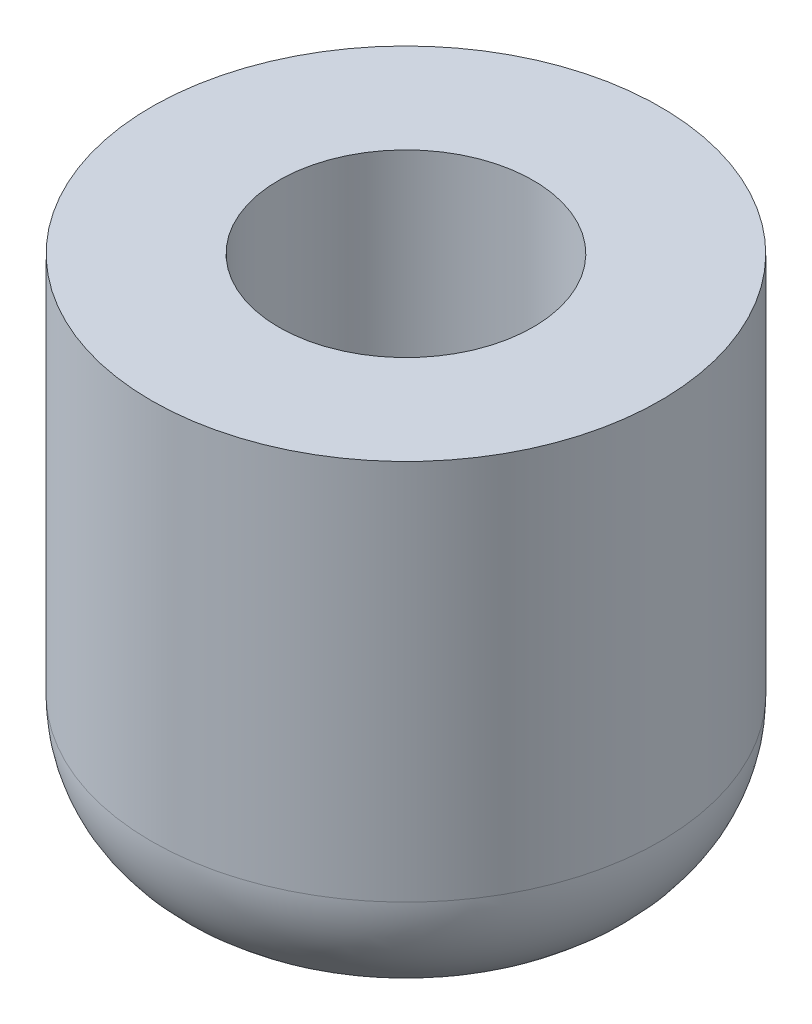
SolidWorks part; units mm, degrees
material "POLYURETHANE (11671)"
ref_plane "Front" through (0, 0, 0) normal (0, 0, 1) x (1, 0, 0)
ref_plane "Top" through (0, 0, 0) normal (0, 1, 0) x (1, 0, 0)
ref_plane "Right" through (0, 0, 0) normal (1, 0, 0) x (0, 0, -1)
sketch "Sketch1" plane through (0, 0, 0) normal (0, 1, 0) x (1, 0, 0)
  circle A0 centre (0, 0) radius 6.35
  dimension "D1" = 12.7
extrude "Boss-Extrude1" add sketch "Sketch1" along normal mid plane 12.7
sketch "Sketch2" plane through (0, 6.35, 0) normal (0, 1, 0) x (1, 0, 0)
  circle A0 centre (0, 0) radius 3.175
  dimension "D1" = 6.35
extrude "Cut-Extrude1" cut sketch "Sketch2" against normal blind 6.35
fillet "Fillet1" radius 3.175 1 edges at (0, -6.35, 6.35)
